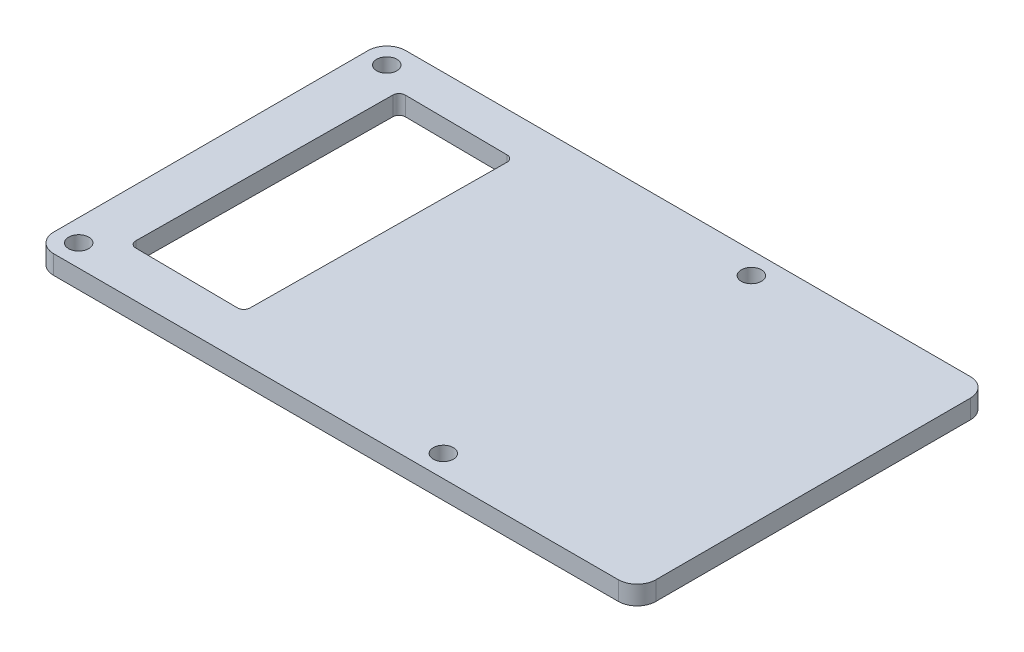
SolidWorks part; units mm, degrees
ref_plane "前视基准面" through (0, 0, 0) normal (0, 0, 1) x (1, 0, 0)
ref_plane "上视基准面" through (0, 0, 0) normal (0, 1, 0) x (1, 0, 0)
ref_plane "右视基准面" through (0, 0, 0) normal (1, 0, 0) x (0, 0, -1)
other "Configuration Table"
sketch "草图1" plane through (0, 0, 0) normal (0, 1, 0) x (1, 0, 0)
  line L8 (-70.9034, 18.2303) -> (-54.5645, 18.0823)
  line L9 (-53.5736, 17.0733) -> (-53.9406, -23.4455)
  line L10 (-54.9496, -24.4364) -> (-71.2885, -24.2884)
  line L11 (-71.9124, 17.2394) -> (-72.2794, -23.2794)
  line L12 (-80.009, 21.4027) -> (-80.009, -28.6044)
  line L13 (-77.0217, -31.5917) -> (12.7873, -31.5917)
  line L14 (15.7746, -28.6044) -> (15.7746, 21.4027)
  line L15 (12.7873, 24.39) -> (-77.0217, 24.39)
  line L16 (-80.009, 21.4027) -> (-80.009, -28.6044)
  line L17 (-77.0217, -31.5917) -> (12.7873, -31.5917)
  line L18 (15.7746, -28.6044) -> (15.7746, 21.4027)
  line L19 (12.7873, 24.39) -> (-77.0217, 24.39)
  circle A4 centre (-76.5285, 20.8867) radius 1.6
  circle A5 centre (-18.5286, 20.8866) radius 1.6
  circle A6 centre (-18.5283, -28.1137) radius 1.6
  circle A7 centre (-76.5283, -28.1135) radius 1.6
  arc A8 (-80.009, -28.6044) -> (-77.0217, -31.5917) centre (-77.0217, -28.6044) ccw
  arc A9 (12.7873, -31.5917) -> (15.7746, -28.6044) centre (12.7873, -28.6044) ccw
  arc A10 (15.7746, 21.4027) -> (12.7873, 24.39) centre (12.7873, 21.4027) ccw
  arc A11 (-77.0217, 24.39) -> (-80.009, 21.4027) centre (-77.0217, 21.4027) ccw
  arc A12 (-80.009, -28.6044) -> (-77.0217, -31.5917) centre (-77.0217, -28.6044) ccw
  arc A13 (12.7873, -31.5917) -> (15.7746, -28.6044) centre (12.7873, -28.6044) ccw
  arc A14 (15.7746, 21.4027) -> (12.7873, 24.39) centre (12.7873, 21.4027) ccw
  arc A15 (-77.0217, 24.39) -> (-80.009, 21.4027) centre (-77.0217, 21.4027) ccw
  arc A16 (-71.2885, -24.2884) -> (-72.2794, -23.2794) centre (-71.2794, -23.2885) cw
  arc A17 (-53.5736, 17.0733) -> (-54.5645, 18.0823) centre (-54.5735, 17.0823) ccw
  arc A18 (-70.9034, 18.2303) -> (-71.9124, 17.2394) centre (-70.9125, 17.2303) ccw
  arc A19 (-53.9406, -23.4455) -> (-54.9496, -24.4364) centre (-54.9405, -23.4364) cw
  dimension "D2" = 3.2
  dimension "D3" = 3.2
  dimension "D4" = 3.2
  dimension "D5" = 3.2
  dimension "D6" = 1
  dimension "D7" = 1
  dimension "D1" = 0
extrude "凸台-拉伸1" add sketch "草图1" along normal blind 3
